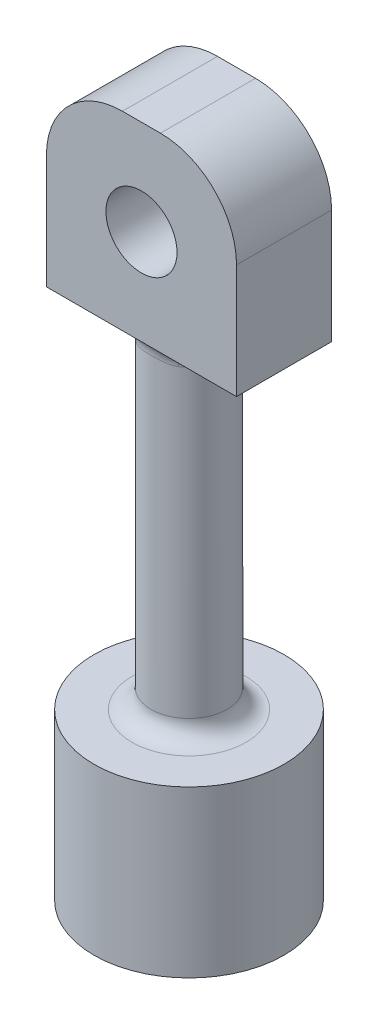
SolidWorks part; units mm, degrees
ref_plane "Front Plane" through (0, 0, 0) normal (0, 0, 1) x (1, 0, 0)
ref_plane "Top Plane" through (0, 0, 0) normal (0, 1, 0) x (1, 0, 0)
ref_plane "Right Plane" through (0, 0, 0) normal (1, 0, 0) x (0, 0, -1)
sketch "Sketch1" plane through (0, 0, 0) normal (0, 1, 0) x (1, 0, 0)
  circle A0 centre (0, 0) radius 0.25
  dimension "D1" = 0.5
extrude "Boss-Extrude1" add sketch "Sketch1" along normal blind 0.435
ref_plane "Plane1" through (0, 0.435, 0) normal (0, 1, 0) x (1, 0, 0)
sketch "Sketch2" plane through (0, 0.435, 0) normal (0, 1, 0) x (1, 0, 0)
  circle A0 centre (0, 0) radius 0.1
  dimension "D1" = 0.2
extrude "Boss-Extrude2" add sketch "Sketch2" along normal blind 0.9
ref_plane "Plane2" through (0, 1.335, 0) normal (0, 1, 0) x (1, 0, 0)
sketch "Sketch3" plane through (0, 1.335, 0) normal (0, 1, 0) x (1, 0, 0)
  line L1 (-0.25, 0.125) -> (0.25, 0.125)
  line L2 (-0.25, 0.125) -> (-0.25, -0.125)
  line L3 (-0.25, -0.125) -> (0.25, -0.125)
  line L4 (0.25, 0.125) -> (0.25, -0.125)
  line L5 (-0.25, 0.125) -> (0.25, -0.125) construction
  line L6 (-0.25, -0.125) -> (0.25, 0.125) construction
  point P0 (0, 0)
  dimension "D1" = 0.5
  dimension "D2" = 0.25
extrude "Boss-Extrude3" add sketch "Sketch3" along normal blind 0.5
fillet "Fillet1" radius 0.2 1 edges at (0.25, 1.835, 0)
fillet "Fillet2" radius 0.2 1 edges at (-0.25, 1.835, 0)
ref_plane "Plane4" through (0, 0, 0.125) normal (0, 0, 1) x (1, 0, 0)
sketch "Sketch5" plane through (0, 0, 0.125) normal (0, 0, 1) x (1, 0, 0)
  line L0 (0, 1.835) -> (0, 1.335) construction
  line L1 (-0.05, 1.835) -> (0.05, 1.835) construction
  line L2 (0.275, 1.335) -> (-0.275, 1.335) construction
  circle A0 centre (0, 1.585) radius 0.0935
  dimension "D1" = 0.187
extrude "Cut-Extrude1" cut sketch "Sketch5" against normal blind 0.25
fillet "Fillet3" radius 0.05 1 edges at (0, 1.335, 0.1)
fillet "Fillet4" radius 0.05 1 edges at (0, 0.435, 0.1)
